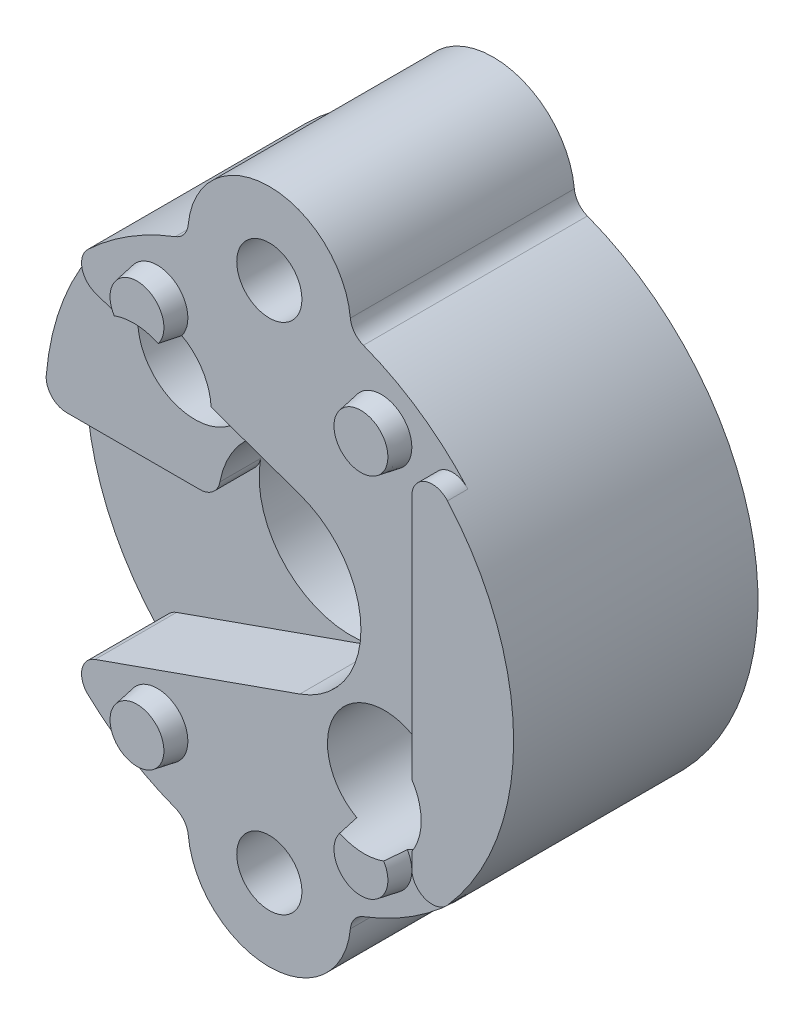
SolidWorks part; units mm, degrees
ref_plane "Front Plane" through (0, 0, 0) normal (0, 0, 1) x (1, 0, 0)
ref_plane "Top Plane" through (0, 0, 0) normal (0, 1, 0) x (1, 0, 0)
ref_plane "Right Plane" through (0, 0, 0) normal (1, 0, 0) x (0, 0, -1)
sketch "Sketch1" plane through (0, 0, 0) normal (0, 0, 1) x (1, 0, 0)
  line L0 (0, -11) -> (0, 11) construction
  line L1 (0, 0) -> (-0.5714, -4.4636) construction
  line L2 (0, 0) -> (0.5714, -4.4636) construction
  line L3 (1.587, -12.3968) -> (0, -16.6) construction
  line L4 (-1.587, -12.3968) -> (0, -16.6) construction
  line L6 (0, 0) -> (-13, 0) construction
  line L7 (-1.587, 12.3968) -> (0, 16.6) construction
  line L8 (1.587, 12.3968) -> (0, 16.6) construction
  arc A0 (3.9935, -12.3714) -> (3.9935, 12.3714) centre (0, 0) ccw
  circle A2 centre (0, 0) radius 4.5
  arc A5 (1.587, -12.3968) -> (-1.587, -12.3968) centre (0, -12.6) ccw
  arc A6 (-1.587, 12.3968) -> (1.587, 12.3968) centre (0, 12.6) ccw
  arc A7 (0, -16.6) -> (3.9935, -12.3714) centre (0, -12.6) ccw
  arc A8 (0, -16.6) -> (-3.9935, -12.3714) centre (0, -12.6) cw
  arc A9 (0, 16.6) -> (-3.9935, 12.3714) centre (0, 12.6) ccw
  arc A10 (0, 16.6) -> (3.9935, 12.3714) centre (0, 12.6) cw
  arc A11 (-3.9935, 12.3714) -> (-3.9935, -12.3714) centre (0, 0) ccw
  arc A16 (1.587, -12.3968) -> (-1.587, -12.3968) centre (0, -12.6) cw
  arc A18 (1.587, 12.3968) -> (-1.587, 12.3968) centre (0, 12.6) ccw
  dimension "D1" = 26
  dimension "D2" = 9
  dimension "D3" = 3.2
  dimension "D4" = 22
  dimension "D5" = 4
extrude "Boss-Extrude1" add sketch "Sketch1" along normal blind 11
sketch "Sketch2" plane through (0, 0, 11) normal (0, 0, 1) x (1, 0, 0)
  line L0 (-9.9988, -8.3081) -> (1.5, -4.2426)
  line L1 (1.5, -4.2426) -> (1.5, 4.2426)
  line L3 (1.5, 4.2426) -> (-9.9988, 8.3081)
  arc A0 (-3.9935, 12.3714) -> (-3.9935, -12.3714) centre (0, 0) ccw construction
  circle A1 centre (0, 0) radius 4.5 construction
  arc A2 (-9.9988, 8.3081) -> (-9.9988, -8.3081) centre (0, 0) ccw
  arc A3 (3.9935, -12.3714) -> (3.9935, 12.3714) centre (0, 0) ccw construction
  dimension "D1" = 1.5
extrude "Cut-Extrude1" cut sketch "Sketch2" against normal blind 2
sketch "Sketch3" plane through (0, 0, 11) normal (0, 0, 1) x (1, 0, 0)
  line L1 (5.5, 9) -> (-5.5, 9) construction
  line L2 (5.5, 9) -> (5.5, -9) construction
  line L3 (5.5, -9) -> (-5.5, -9) construction
  line L4 (-5.5, 9) -> (-5.5, -9) construction
  line L5 (5.5, 9) -> (-5.5, -9) construction
  line L6 (5.5, -9) -> (-5.5, 9) construction
  circle A0 centre (-5.5, -9) radius 1.5
  circle A1 centre (5.5, -9) radius 1.5
  circle A2 centre (5.5, 9) radius 1.5
  circle A3 centre (-5.5, 9) radius 1.5
  point P0 (0, 0)
  dimension "D3" = 3
  dimension "D1" = 11
  dimension "D2" = 18
extrude "Boss-Extrude2" add sketch "Sketch3" along normal blind 1 draft 10
sketch "Sketch4" plane through (0, 0, 11) normal (0, 0, 1) x (1, 0, 0)
  line L1 (-5.6569, 5.6569) -> (5.6569, 5.6569) construction
  line L2 (-5.6569, 5.6569) -> (-5.6569, -5.6569) construction
  line L3 (-5.6569, -5.6569) -> (5.6569, -5.6569) construction
  line L4 (5.6569, 5.6569) -> (5.6569, -5.6569) construction
  line L5 (-5.6569, 5.6569) -> (5.6569, -5.6569) construction
  line L6 (-5.6569, -5.6569) -> (5.6569, 5.6569) construction
  circle A0 centre (5.6569, -5.6569) radius 1.6
  circle A1 centre (-5.6569, 5.6569) radius 1.6
  point P0 (0, 0)
  dimension "D2" = 3.2
  dimension "D1" = 16
extrude "Cut-Extrude2" cut sketch "Sketch4" against normal through all
sketch "Sketch5" plane through (0, 0, 11) normal (0, 0, 1) x (1, 0, 0)
  circle A0 centre (5.6569, -5.6569) radius 2.8
  circle A1 centre (-5.6569, 5.6569) radius 2.8
  dimension "D1" = 5.6
extrude "Cut-Extrude3" cut sketch "Sketch5" against normal blind 5 and the other way through all
sketch "Sketch6" plane through (0, 0, 0) normal (0, 0, -1) x (-1, 0, 0)
  line L1 (0, 9.3668) -> (2.8, 10.9834)
  line L2 (2.8, 10.9834) -> (2.8, 14.2166)
  line L3 (2.8, 14.2166) -> (0, 15.8332)
  line L4 (0, 15.8332) -> (-2.8, 14.2166)
  line L5 (-2.8, 14.2166) -> (-2.8, 10.9834)
  line L6 (-2.8, 10.9834) -> (0, 9.3668)
  line L7 (0, -9.3668) -> (-2.8, -10.9834)
  line L8 (-2.8, -10.9834) -> (-2.8, -14.2166)
  line L9 (-2.8, -14.2166) -> (0, -15.8332)
  line L10 (0, -15.8332) -> (2.8, -14.2166)
  line L11 (2.8, -14.2166) -> (2.8, -10.9834)
  line L12 (2.8, -10.9834) -> (0, -9.3668)
  circle A0 centre (0, 12.6) radius 2.8 construction
  circle A1 centre (0, -12.6) radius 2.8 construction
  dimension "D1" = 5.6
  dimension "D2" = 5.6
extrude "Cut-Extrude4" cut sketch "Sketch6" against normal blind 3
sketch "Sketch7" plane through (0, 0, 9) normal (0, 0, 1) x (1, 0, 0)
  line L0 (-4.5, 0) -> (-13, 0)
  line L2 (-9.9988, -8.3081) -> (1.5, -4.2426) construction
  line L3 (-9.9988, -8.3081) -> (1.5, -4.2426)
  arc A0 (1.5, 4.2426) -> (1.5, -4.2426) centre (0, 0) ccw construction
  arc A1 (-9.9988, 8.3081) -> (-9.9988, -8.3081) centre (0, 0) ccw construction
  arc A2 (-13, 0) -> (-9.9988, -8.3081) centre (0, 0) ccw
  arc A3 (-4.5, 0) -> (1.5, -4.2426) centre (0, 0) ccw
  arc A4 (-9.9988, 8.3081) -> (-9.9988, -8.3081) centre (0, 0) ccw construction
extrude "Cut-Extrude5" cut sketch "Sketch7" against normal blind 2
sketch "Sketch8" plane through (0, 0, 11) normal (0, 0, 1) x (1, 0, 0)
  line L0 (8, 10.247) -> (8, -4.124)
  line L1 (8, -7.1897) -> (8, -10.247)
  arc A0 (3.9935, -12.3714) -> (3.9935, 12.3714) centre (0, 0) ccw construction
  arc A1 (8, -10.247) -> (8, 10.247) centre (0, 0) ccw
  arc A2 (6.7818, -8.2209) -> (4.2968, -8.1043) centre (5.6569, -5.6569) ccw construction
  arc A3 (8, -7.1897) -> (8, -4.124) centre (5.6569, -5.6569) ccw
  dimension "D1" = 8
extrude "Boss-Extrude3" add sketch "Sketch8" along normal blind 1
sketch "Sketch9" plane through (0, 0, 0) normal (0, 0, -1) x (-1, 0, 0)
  line L0 (0, 0) -> (5.6569, -5.6569) construction
  line L1 (5.7403, -7.1545) -> (8.458, -9.8723)
  line L2 (7.1545, -5.7403) -> (9.8723, -8.458)
  arc A0 (7.1545, -5.7403) -> (5.7403, -7.1545) centre (5.6569, -5.6569) ccw
  arc A4 (3.9935, -12.3714) -> (3.9935, 12.3714) centre (0, 0) ccw construction
  arc A5 (8.458, -9.8723) -> (9.8723, -8.458) centre (0, 0) ccw
  point P5 (5.6569, 5.6569)
  point P9 (-5.6569, -5.6569)
  dimension "D1" = 3
  dimension "D2" = 2
  dimension "D3" = 2
extrude "Cut-Extrude6" cut sketch "Sketch9" against normal blind 1
fillet "Fillet1" radius 1 12 edges at (-3.9935, 12.3714, 5.5) (3.9935, 12.3714, 5.5) (-3.9935, -12.3714, 5.5) (3.9935, -12.3714, 5.5) (-9.9988, -8.3081, 9) (-9.9988, 8.3081, 10) (-4.5, 0, 8) (-13, 0, 8) (8, 10.247, 11.5) (8, -10.247, 11.5) (-5.7403, -7.1545, 0.5) (-7.1545, -5.7403, 0.5)
sketch "Sketch10" plane through (0, 0, 0) normal (0, 0, -1) x (-1, 0, 0)
  line L0 (5, 2.8868) -> (6.5588, 1.9868) construction
  line L1 (5.5, 3.7528) -> (7.0588, 2.8528)
  line L2 (4.5, 2.0207) -> (6.0588, 1.1207)
  line L3 (0, 0) -> (4.0351, 0) construction
  arc A0 (5.5, 3.7528) -> (4.5, 2.0207) centre (5, 2.8868) ccw
  arc A1 (6.0588, 1.1207) -> (7.0588, 2.8528) centre (6.5588, 1.9868) ccw
  point P2 (5.7794, 2.4368)
  dimension "D1" = 30
  dimension "D2" = 5
  dimension "D3" = 2
  dimension "D4" = 1.8
  dimension "D5" = 5
extrude "Cut-Extrude7" cut sketch "Sketch10" against normal blind 2
equation "\"D3@Sketch9\"=\"D2@Sketch9\""
